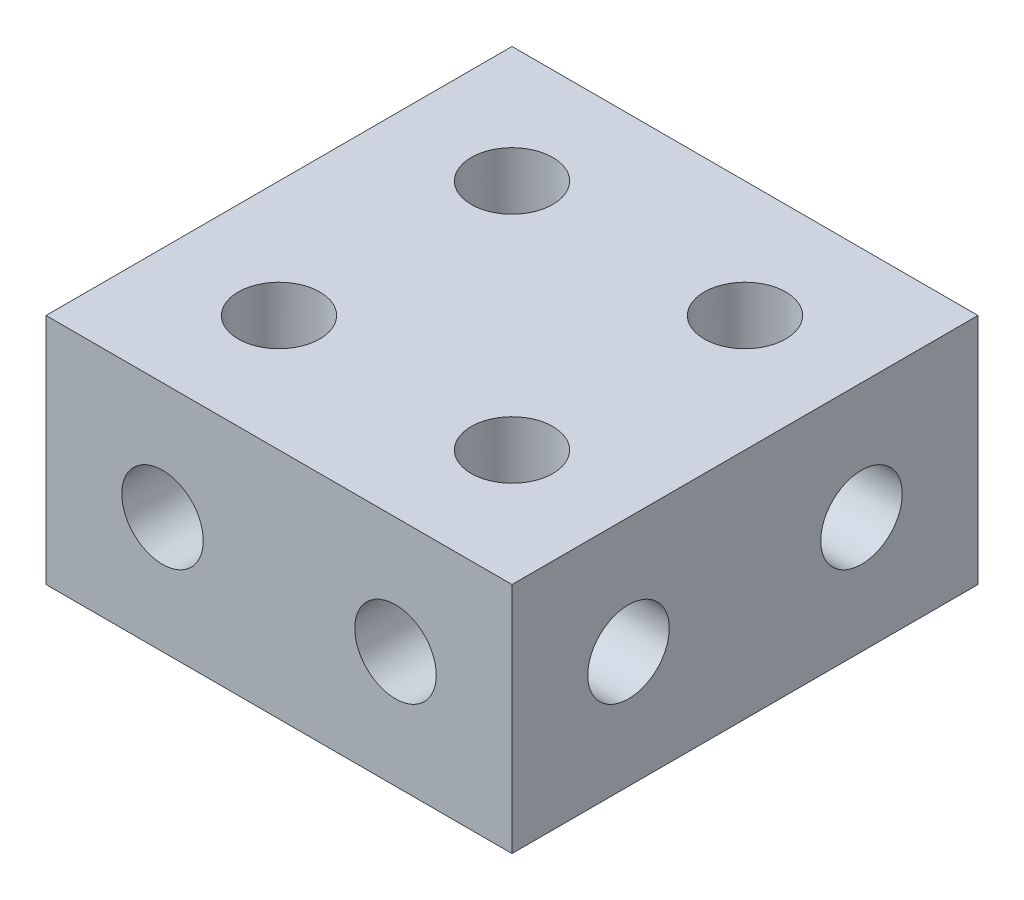
SolidWorks part; units mm, degrees
ref_plane "Plan de face" through (0, 0, 0) normal (0, 0, 1) x (1, 0, 0)
ref_plane "Plan de dessus" through (0, 0, 0) normal (0, 1, 0) x (1, 0, 0)
ref_plane "Plan de droite" through (0, 0, 0) normal (1, 0, 0) x (0, 0, -1)
sketch "Esquisse1" plane through (0, 0, 0) normal (1, 0, 0) x (0, 0, -1)
  line L1 (0, 0) -> (20, 0)
  line L2 (0, 0) -> (0, 10)
  line L3 (0, 10) -> (20, 10)
  line L4 (20, 0) -> (20, 10)
  dimension "D1" = 20
  dimension "D2" = 10
extrude "Boss.-Extru.1" add sketch "Esquisse1" along normal blind 20
sketch "Esquisse2" plane through (0, 10, 0) normal (0, 1, 0) x (1, 0, 0)
  line L0 (0, 15) -> (40, 15) construction
  line L4 (20, 20) -> (0, 20) construction
  circle A0 centre (5, 15) radius 1.75
  circle A1 centre (15, 15) radius 1.75
  circle A2 centre (25, 15) radius 1.75
  circle A3 centre (35, 15) radius 1.75
  circle A4 centre (5, 5) radius 1.75
  circle A5 centre (15, 5) radius 1.75
  circle A6 centre (25, 5) radius 1.75
  circle A7 centre (35, 5) radius 1.75
  circle A8 centre (5, -5) radius 1.75
  circle A9 centre (15, -5) radius 1.75
  circle A10 centre (25, -5) radius 1.75
  circle A11 centre (35, -5) radius 1.75
  circle A12 centre (5, -15) radius 1.75
  circle A13 centre (15, -15) radius 1.75
  circle A14 centre (25, -15) radius 1.75
  circle A15 centre (35, -15) radius 1.75
  dimension "D4" = 3.5
  dimension "D1" = 5
  dimension "D2" = 10
  dimension "D3" = 10
  dimension "D5" = 10
  dimension "D6" = 5
  dimension "D7" = 4
extrude "Enlèv. mat.-Extru.1" cut sketch "Esquisse2" against normal through all
sketch "Esquisse3" plane through (0, 0, 0) normal (0, 0, 1) x (1, 0, 0)
  line L0 (0, 5) -> (20, 5) construction
  line L1 (0, 10) -> (0, 0) construction
  line L2 (20, 10) -> (20, 0) construction
  circle A0 centre (5, 5) radius 1.75
  circle A1 centre (15, 5) radius 1.75
  circle A2 centre (25, 5) radius 1.75
  circle A3 centre (35, 5) radius 1.75
  dimension "D4" = 3.5
  dimension "D1" = 5
  dimension "D2" = 10
  dimension "D3" = 10
  dimension "D5" = 10
extrude "Enlèv. mat.-Extru.2" cut sketch "Esquisse3" against normal blind 40
sketch "Esquisse4" plane through (20, 0, 0) normal (1, 0, 0) x (0, 0, -1)
  line L0 (0, 5) -> (20, 5) construction
  line L1 (0, 10) -> (0, 0) construction
  line L2 (20, 0) -> (20, 10) construction
  circle A0 centre (5, 5) radius 1.75
  circle A1 centre (15, 5) radius 1.75
  circle A2 centre (25, 5) radius 1.75
  circle A3 centre (35, 5) radius 1.75
  dimension "D1" = 3.5
  dimension "D2" = 5
  dimension "D3" = 4
extrude "Enlèv. mat.-Extru.3" cut sketch "Esquisse4" against normal blind 40
